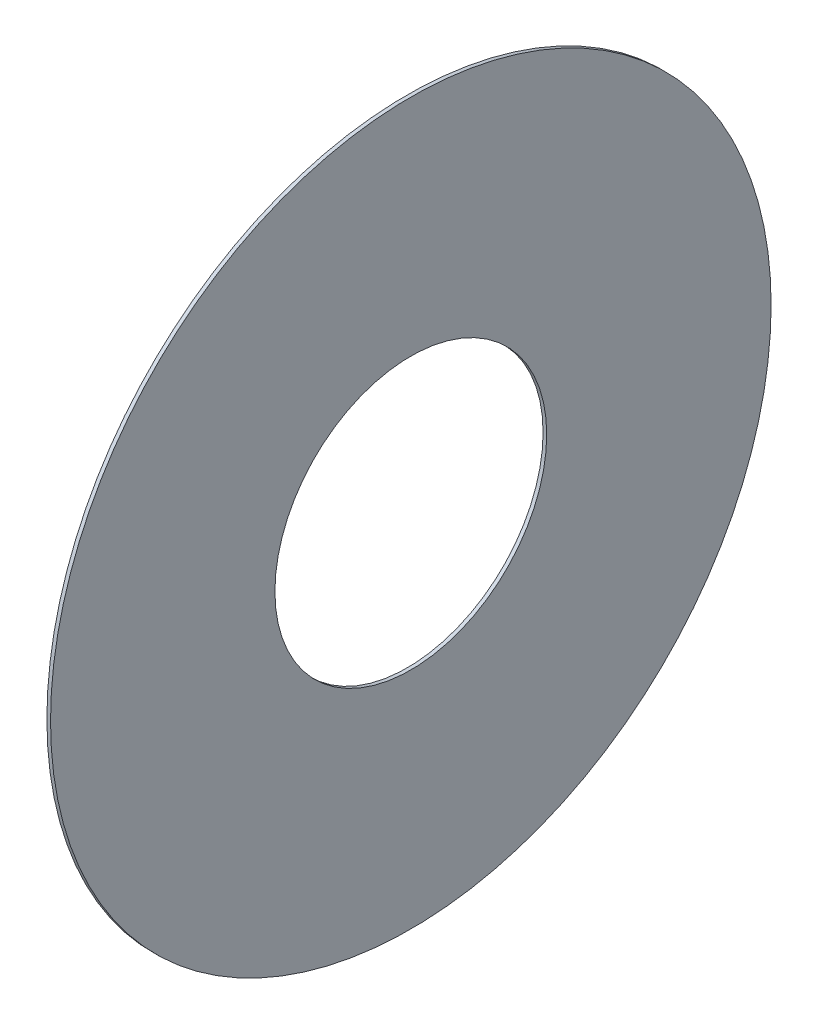
SolidWorks part; units mm, degrees
ref_plane "Front Plane" through (0, 0, 0) normal (0, 0, 1) x (1, 0, 0)
ref_plane "Top Plane" through (0, 0, 0) normal (0, 1, 0) x (1, 0, 0)
ref_plane "Right Plane" through (0, 0, 0) normal (1, 0, 0) x (0, 0, -1)
sketch "Sketch1" plane through (0, 0, 0) normal (1, 0, 0) x (0, 0, -1)
  circle A0 centre (0, 0) radius 60.1701
  circle A1 centre (0, 0) radius 22.6974
  dimension "D1" = 120.3401
  dimension "D2" = 45.3949
extrude "Boss-Extrude1" add sketch "Sketch1" along normal blind 0.6071
